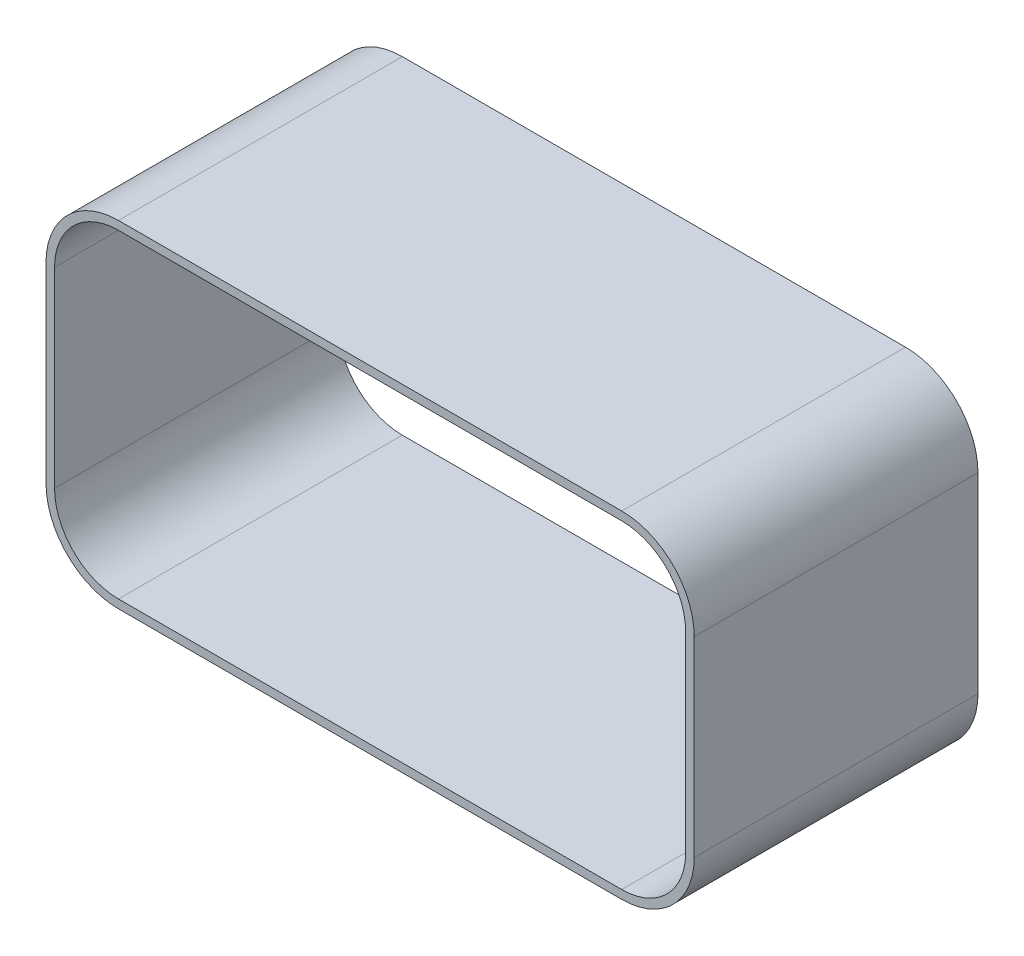
SolidWorks part; units mm, degrees
ref_plane "Front Plane" through (0, 0, 0) normal (0, 0, 1) x (1, 0, 0)
ref_plane "Top Plane" through (0, 0, 0) normal (0, 1, 0) x (1, 0, 0)
ref_plane "Right Plane" through (0, 0, 0) normal (1, 0, 0) x (0, 0, -1)
sketch "Sketch1" plane through (0, 0, 0) normal (0, 0, 1) x (1, 0, 0)
  line L0 (-88.2163, 55.9727) -> (88.2163, 55.9727)
  line L1 (110.6416, 33.5473) -> (110.6416, -33.5473)
  line L2 (88.2163, -55.9727) -> (-88.2163, -55.9727)
  line L3 (-110.6416, -33.5473) -> (-110.6416, 33.5473)
  line L8 (-88.2163, 58.9727) -> (88.2163, 58.9727)
  line L9 (113.6416, 33.5473) -> (113.6416, -33.5473)
  line L10 (88.2163, -58.9727) -> (-88.2163, -58.9727)
  line L11 (-113.6416, -33.5473) -> (-113.6416, 33.5473)
  arc A0 (110.6416, 33.5473) -> (88.2163, 55.9727) centre (88.2163, 33.5473) ccw
  arc A1 (88.2163, -55.9727) -> (110.6416, -33.5473) centre (88.2163, -33.5473) ccw
  arc A2 (-110.6416, -33.5473) -> (-88.2163, -55.9727) centre (-88.2163, -33.5473) ccw
  arc A3 (-88.2163, 55.9727) -> (-110.6416, 33.5473) centre (-88.2163, 33.5473) ccw
  arc A8 (113.6416, 33.5473) -> (88.2163, 58.9727) centre (88.2163, 33.5473) ccw
  arc A9 (88.2163, -58.9727) -> (113.6416, -33.5473) centre (88.2163, -33.5473) ccw
  arc A10 (-113.6416, -33.5473) -> (-88.2163, -58.9727) centre (-88.2163, -33.5473) ccw
  arc A11 (-88.2163, 58.9727) -> (-113.6416, 33.5473) centre (-88.2163, 33.5473) ccw
  dimension "D1" = 3
extrude "Boss-Extrude1" add sketch "Sketch1" along normal blind 99.5
